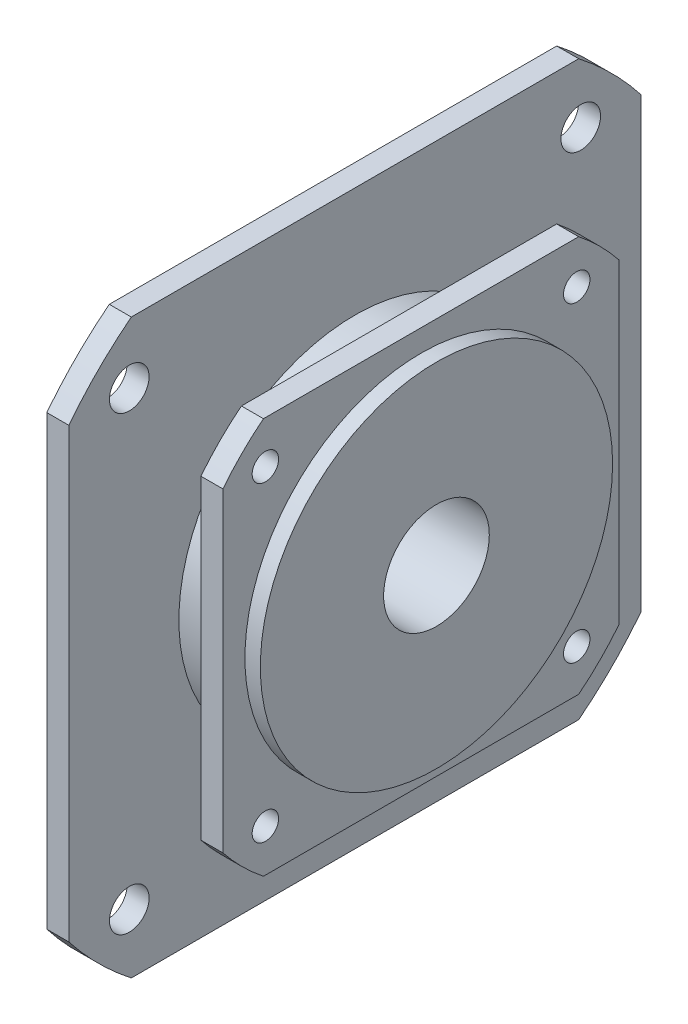
SolidWorks part; units mm, degrees
ref_plane "前视基准面" through (0, 0, 0) normal (0, 0, 1) x (1, 0, 0)
ref_plane "上视基准面" through (0, 0, 0) normal (0, 1, 0) x (1, 0, 0)
ref_plane "右视基准面" through (0, 0, 0) normal (1, 0, 0) x (0, 0, -1)
sketch "草图1" plane through (0, 0, 0) normal (1, 0, 0) x (0, 0, -1)
  line L0 (-34.2254, 0) -> (23.4171, 0) construction
  line L1 (50.806, -65) -> (-50.806, -65)
  line L2 (65, -50.806) -> (65, 50.806)
  line L3 (50.806, 65) -> (-50.806, 65)
  line L4 (-65, -50.806) -> (-65, 50.806)
  line L5 (65, -65) -> (-65, 65) construction
  line L6 (65, 65) -> (-65, -65) construction
  circle A0 centre (0, 0) radius 72.5 construction
  arc A1 (-50.806, 65) -> (-65, 50.806) centre (0, 0) ccw
  arc A2 (65, 50.806) -> (50.806, 65) centre (0, 0) ccw
  arc A3 (50.806, -65) -> (65, -50.806) centre (0, 0) ccw
  arc A4 (-65, -50.806) -> (-50.806, -65) centre (0, 0) ccw
  circle A5 centre (-51.2652, 51.2652) radius 4.5
  circle A6 centre (51.2652, -51.2652) radius 4.5
  circle A7 centre (51.2652, 51.2652) radius 4.5
  circle A8 centre (-51.2652, -51.2652) radius 4.5
  point P0 (0, 0)
  dimension "D3" = 145
  dimension "D4" = 165
  dimension "D5" = 65
  dimension "D9" = 9
  dimension "D1" = 130
  dimension "D2" = 130
  dimension "D6" = 65
  dimension "D7" = 130
  dimension "D8" = 130
extrude "凸台-拉伸1" add sketch "草图1" along normal blind 5
sketch "草图2" plane through (0, 0, 0) normal (-1, 0, 0) x (0, 0, 1)
  circle A0 centre (0, 0) radius 55
  dimension "D1" = 110
extrude "切除-拉伸1" cut sketch "草图2" against normal blind 3
sketch "草图3" plane through (5, 0, 0) normal (1, 0, 0) x (0, 0, -1)
  circle A0 centre (0, 0) radius 40
  dimension "D1" = 80
extrude "凸台-拉伸2" add sketch "草图3" along normal blind 10
sketch "草图4" plane through (15, 0, 0) normal (1, 0, 0) x (0, 0, -1)
  line L0 (8.2843, 0) -> (-21.541, 0) construction
  line L1 (35.7946, -45) -> (-35.7946, -45)
  line L2 (45, -35.7946) -> (45, 35.7946)
  line L3 (35.7946, 45) -> (-35.7946, 45)
  line L4 (-45, -35.7946) -> (-45, 35.7946)
  line L5 (45, -45) -> (-45, 45) construction
  line L6 (45, 45) -> (-45, -45) construction
  arc A0 (-35.7946, 45) -> (-45, 35.7946) centre (0, 0) ccw
  arc A1 (-45, -35.7946) -> (-35.7946, -45) centre (0, 0) ccw
  arc A2 (35.7946, -45) -> (45, -35.7946) centre (0, 0) ccw
  arc A3 (45, 35.7946) -> (35.7946, 45) centre (0, 0) ccw
  circle A4 centre (0, 0) radius 50 construction
  circle A5 centre (-35.3553, 35.3553) radius 3
  circle A6 centre (35.3553, -35.3553) radius 3
  circle A7 centre (35.3553, 35.3553) radius 3
  circle A8 centre (-35.3553, -35.3553) radius 3
  point P0 (0, 0)
  dimension "D3" = 115
  dimension "D8" = 100
  dimension "D9" = 6
  dimension "D1" = 90
  dimension "D2" = 90
  dimension "D4" = 90
  dimension "D5" = 45
  dimension "D6" = 45
  dimension "D7" = 90
extrude "凸台-拉伸3" add sketch "草图4" along normal blind 5
sketch "草图5" plane through (20, 0, 0) normal (1, 0, 0) x (0, 0, -1)
  circle A0 centre (0, 0) radius 40
  dimension "D1" = 80
extrude "凸台-拉伸4" add sketch "草图5" along normal blind 3.5
sketch "草图6" plane through (23.5, 0, 0) normal (1, 0, 0) x (0, 0, -1)
  circle A0 centre (0, 0) radius 12
  dimension "D1" = 24
extrude "切除-拉伸2" cut sketch "草图6" against normal through all
